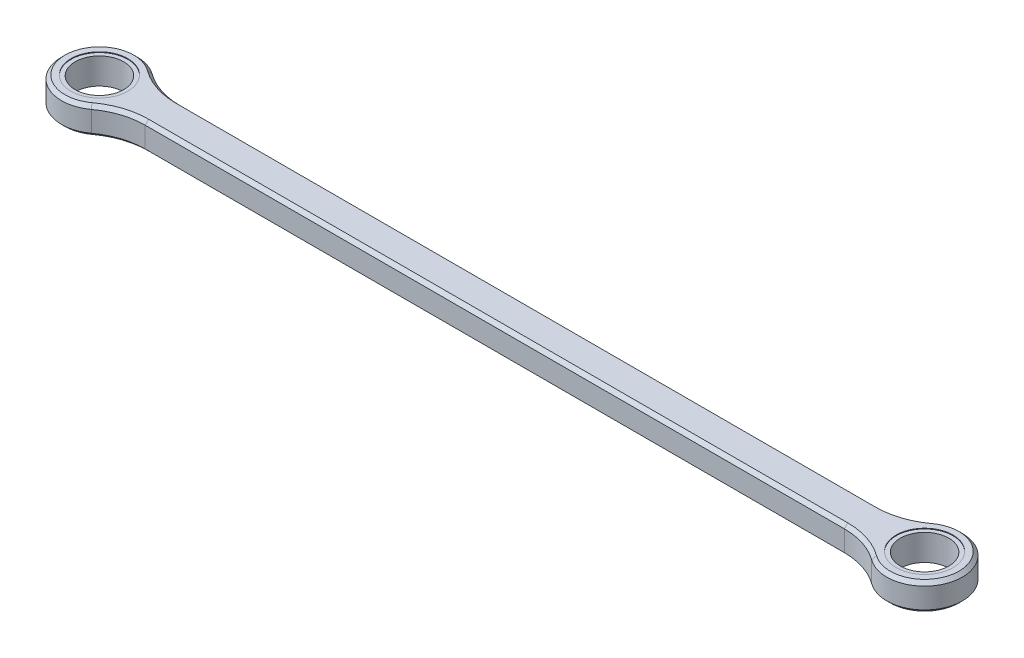
SolidWorks part; units mm, degrees
ref_plane "前视基准面" through (0, 0, 0) normal (0, 0, 1) x (1, 0, 0)
ref_plane "上视基准面" through (0, 0, 0) normal (0, 1, 0) x (1, 0, 0)
ref_plane "右视基准面" through (0, 0, 0) normal (1, 0, 0) x (0, 0, -1)
other "Configuration Table"
sketch "草图1" plane through (0, 0, 0) normal (0, 1, 0) x (1, 0, 0)
  line L0 (0, 0) -> (120, 0) construction
  line L2 (4.899, 2.5) -> (115.101, 2.5)
  line L3 (4.899, 2.5) -> (4.899, -2.5) construction
  line L4 (4.899, -2.5) -> (115.101, -2.5)
  line L5 (115.101, 2.5) -> (115.101, -2.5) construction
  line L6 (60, -2.5) -> (60, 2.5) construction
  line L7 (4.899, 0) -> (115.101, 0) construction
  circle A0 centre (0, 0) radius 5.5 construction
  circle A1 centre (120, 0) radius 5.5 construction
  circle A2 centre (0, 0) radius 3.525
  circle A3 centre (120, 0) radius 3.525
  arc A4 (4.899, 2.5) -> (4.899, -2.5) centre (0, 0) ccw
  arc A5 (115.101, 2.5) -> (115.101, -2.5) centre (120, 0) cw
  point P7 (60, 0)
  dimension "D1" = 11
  dimension "D3" = 11
  dimension "D4" = 7.05
  dimension "D5" = 7.05
  dimension "D2" = 120
  dimension "D6" = 5
extrude "凸台-拉伸1" add sketch "草图1" along normal blind 4
fillet "圆角1" radius 10 4 edges at (115.101, 2, 2.5) (115.101, 2, -2.5) (4.899, 2, 2.5) (4.899, 2, -2.5)
sketch "草图2" plane through (0, 4, 0) normal (0, 1, 0) x (1, 0, 0)
  line L0 (110.8348, 2.5) -> (9.1652, 2.5) construction
  line L1 (9.1652, -2.5) -> (110.8348, -2.5) construction
  line L2 (60, 2.5) -> (60, -2.5) construction
  line L3 (110, 0) -> (10, 0) construction
  line L4 (110, -1.25) -> (10, -1.25)
  line L5 (110, 1.25) -> (10, 1.25)
  arc A6 (110, -1.25) -> (110, 1.25) centre (110, 0) ccw
  arc A7 (10, 1.25) -> (10, -1.25) centre (10, 0) ccw
  point P5 (60, 0)
  dimension "D1" = 50
  dimension "D2" = 2.5
extrude "切除-拉伸1" [suppressed] cut sketch "草图2" against normal blind 2
chamfer "倒角1" distance 0.5 angle 45 16 edges at (60, 0, 2.5) (113.9457, 0, 2.9962) (6.0543, 0, 2.9962) (125.5, 0, 0) (-5.5, 0, 0) (113.9457, 0, -2.9962) (6.0543, 0, -2.9962) (60, 0, -2.5) (60, 4, 2.5) (113.9457, 4, 2.9962) (6.0543, 4, 2.9962) (125.5, 4, 0) (-5.5, 4, 0) (113.9457, 4, -2.9962) (6.0543, 4, -2.9962) (60, 4, -2.5)
sketch "草图3" plane through (0, 4, 0) normal (0, 1, 0) x (1, 0, 0)
  circle A0 centre (0, 0) radius 4.125
  circle A1 centre (120, 0) radius 4.125
  dimension "D1" = 8.25
  dimension "D2" = 8.25
extrude "切除-拉伸2" cut sketch "草图3" against normal blind 0.1
sketch "草图4" plane through (0, 0, 0) normal (0, -1, 0) x (1, 0, 0)
  circle A0 centre (0, 0) radius 4.125
  circle A1 centre (120, 0) radius 4.125
  dimension "D1" = 8.25
  dimension "D2" = 8.25
extrude "切除-拉伸3" cut sketch "草图4" against normal blind 0.1
